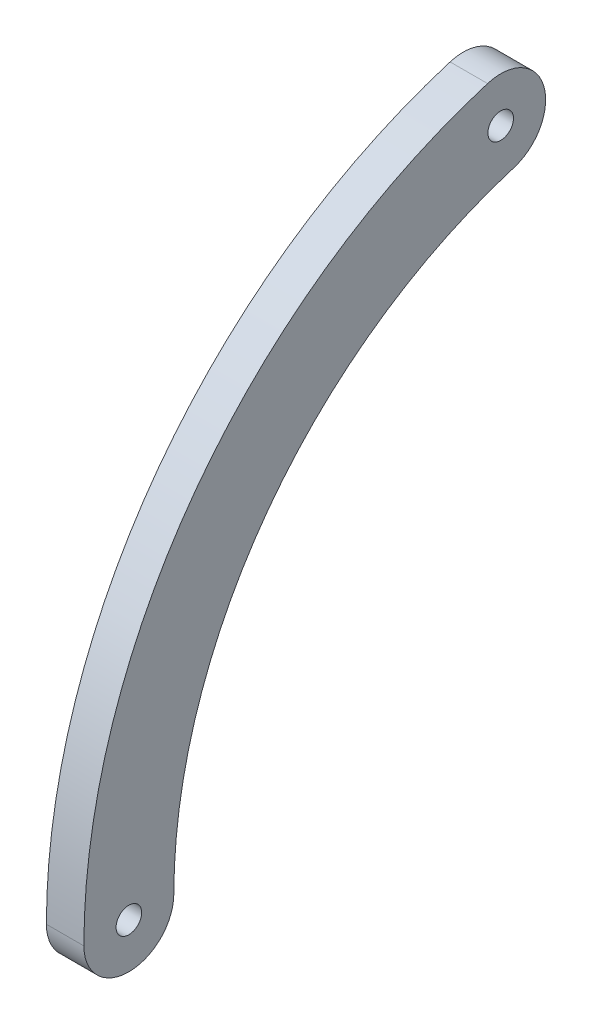
SolidWorks part; units mm, degrees
material "ABS"
ref_plane "Front Plane" through (0, 0, 0) normal (0, 0, 1) x (1, 0, 0)
ref_plane "Top Plane" through (0, 0, 0) normal (0, 1, 0) x (1, 0, 0)
ref_plane "Right Plane" through (0, 0, 0) normal (1, 0, 0) x (0, 0, -1)
sketch "Esquisse1" plane through (0, 0, 0) normal (1, 0, 0) x (0, 0, -1)
  arc A0 (-48.768, 0) -> (-14.2102, 46.6518) centre (0, 0) cw
  arc A1 (-57.912, 0) -> (-16.8746, 55.399) centre (0, 0) cw
  arc A2 (-57.912, 0) -> (-48.768, 0) centre (-53.34, 0) ccw
  arc A3 (-14.2102, 46.6518) -> (-16.8746, 55.399) centre (-15.5424, 51.0254) ccw
  circle A4 centre (-53.34, 0) radius 1.3
  circle A5 centre (-15.5424, 51.0254) radius 1.3
  dimension "D1" = 4.572
  dimension "D4" = 2.6
  dimension "D5" = 2.6
  dimension "D2" = 63.5
  dimension "D3" = 53.34
extrude "Boss.-Extru.1" add sketch "Esquisse1" along normal blind 3.81
